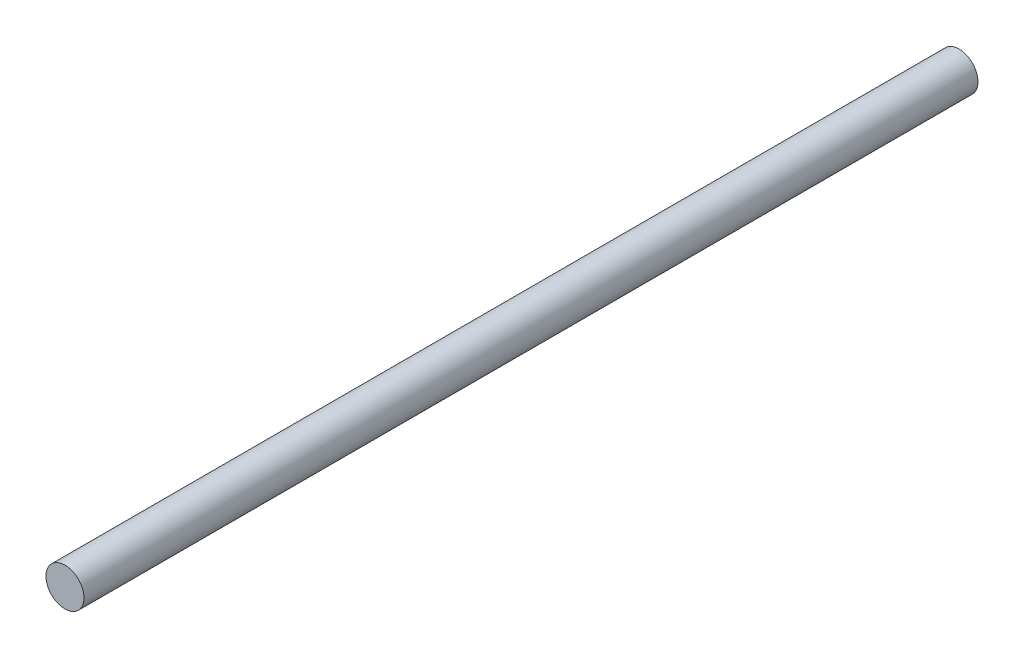
SolidWorks part; units mm, degrees
ref_plane "Front Plane" through (0, 0, 0) normal (0, 0, 1) x (1, 0, 0)
ref_plane "Top Plane" through (0, 0, 0) normal (0, 1, 0) x (1, 0, 0)
ref_plane "Right Plane" through (0, 0, 0) normal (1, 0, 0) x (0, 0, -1)
sketch "Sketch1" plane through (0, 0, 0) normal (0, 0, 1) x (1, 0, 0)
  circle A0 centre (0, 0) radius 3.175
  dimension "D1" = 6.35
extrude "Boss-Extrude1" add sketch "Sketch1" along normal blind 149.352
